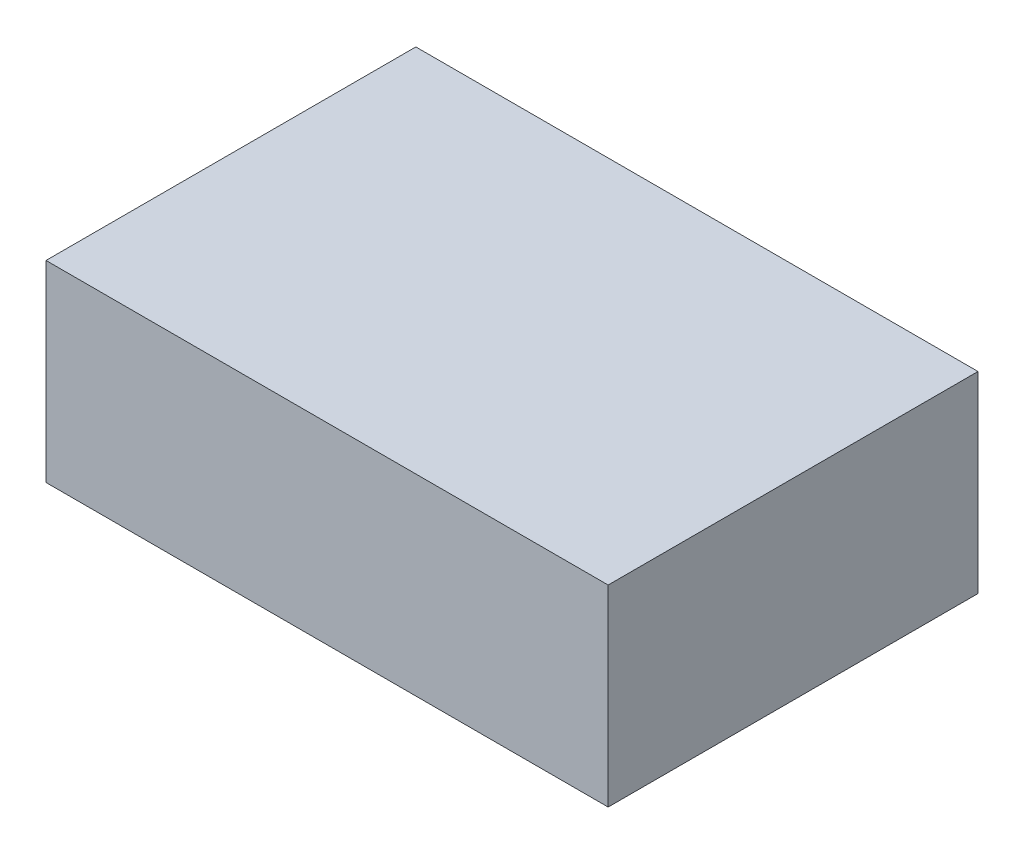
SolidWorks part; units mm, degrees
ref_plane "前视基准面" through (0, 0, 0) normal (0, 0, 1) x (1, 0, 0)
ref_plane "上视基准面" through (0, 0, 0) normal (0, 1, 0) x (1, 0, 0)
ref_plane "右视基准面" through (0, 0, 0) normal (1, 0, 0) x (0, 0, -1)
sketch "草图1" plane through (0, 0, 0) normal (0, 1, 0) x (1, 0, 0)
  line L0 (-76, -50) -> (76, -50)
  line L1 (-76, -50) -> (-76, 50)
  line L2 (76, -50) -> (76, 50)
  line L3 (-76, 50) -> (76, 50)
  line L4 (-76, -50) -> (76, 50) construction
  line L5 (76, -50) -> (-76, 50) construction
  point P1 (0, 0)
  dimension "D1" = 152
  dimension "D2" = 100
extrude "凸台-拉伸1" add sketch "草图1" along normal blind 52
